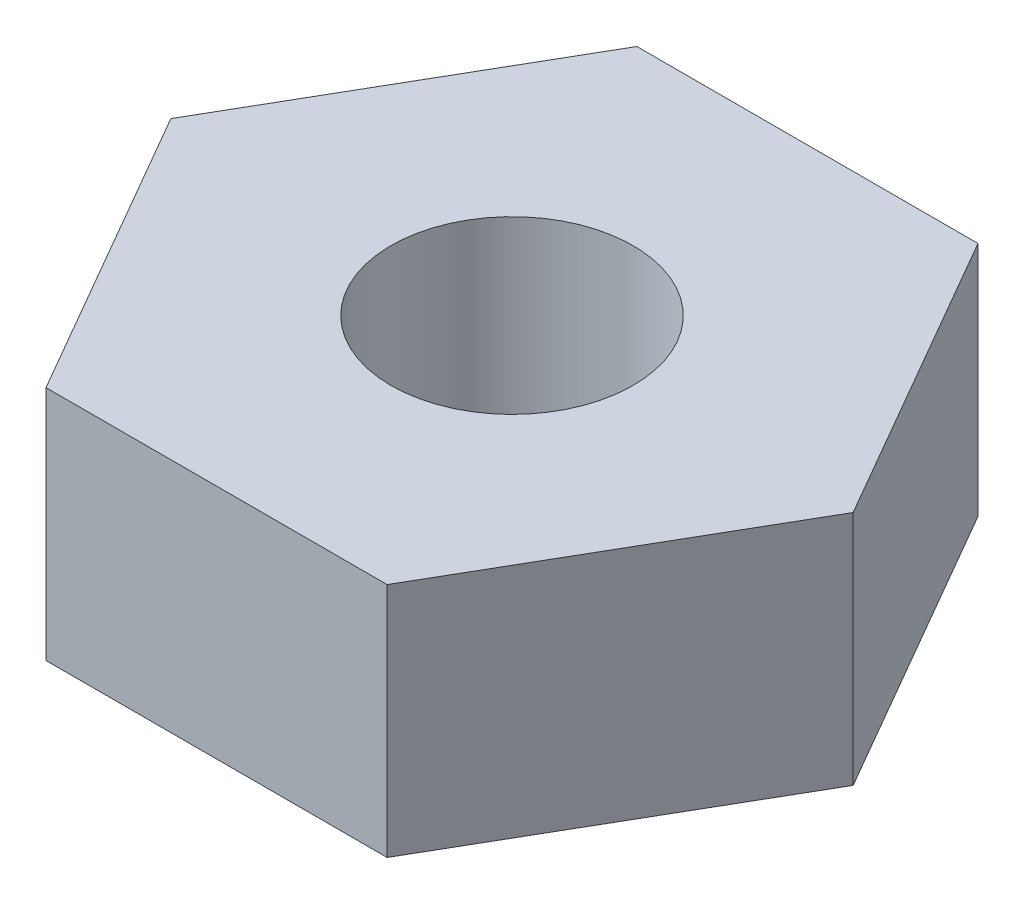
SolidWorks part; units mm, degrees
material "acero"
ref_plane "Alzado" through (0, 0, 0) normal (0, 0, 1) x (1, 0, 0)
ref_plane "Planta" through (0, 0, 0) normal (0, 1, 0) x (1, 0, 0)
ref_plane "Vista lateral" through (0, 0, 0) normal (1, 0, 0) x (0, 0, -1)
sketch "Croquis1" plane through (0, 0, 0) normal (0, 1, 0) x (1, 0, 0)
  line L1 (-1.4434, 2.5) -> (-2.8868, 0)
  line L2 (-2.8868, 0) -> (-1.4434, -2.5)
  line L3 (-1.4434, -2.5) -> (1.4434, -2.5)
  line L4 (1.4434, -2.5) -> (2.8868, 0)
  line L5 (2.8868, 0) -> (1.4434, 2.5)
  line L6 (1.4434, 2.5) -> (-1.4434, 2.5)
  circle A0 centre (0, 0) radius 2.5 construction
  circle A1 centre (0, 0) radius 1.025
  dimension "D1" = 2.05
  dimension "D2" = 5
extrude "Saliente-Extruir1" add sketch "Croquis1" along normal blind 2
cosmetic thread "Rosca cosmética1" parameters "D2"=2.5
